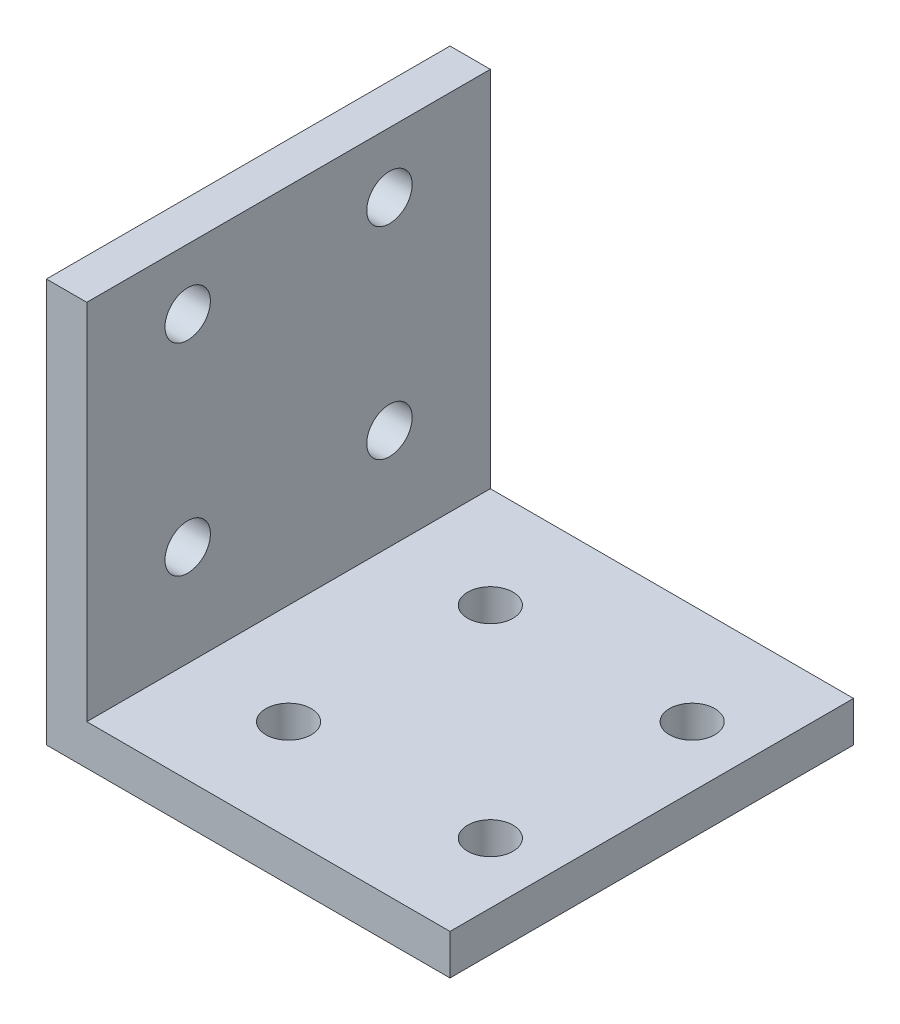
SolidWorks part; units mm, degrees
material "Д16Т ГОСТ 4784-74"
ref_plane "Спереди" through (0, 0, 0) normal (0, 0, 1) x (1, 0, 0)
ref_plane "Сверху" through (0, 0, 0) normal (0, 1, 0) x (1, 0, 0)
ref_plane "Справа" through (0, 0, 0) normal (1, 0, 0) x (0, 0, -1)
sketch "Эскиз1" plane through (0, 0, 0) normal (0, 0, 1) x (1, 0, 0)
  line L0 (0, 0) -> (0, 40)
  line L1 (0, 40) -> (4, 40)
  line L2 (4, 40) -> (4, 4)
  line L3 (4, 4) -> (40, 4)
  line L4 (40, 4) -> (40, 0)
  line L5 (40, 0) -> (0, 0)
  dimension "D1" = 40
  dimension "D2" = 4
extrude "Бобышка-Вытянуть1" add sketch "Эскиз1" along normal blind 40
hole_wizard "Отверстие с зазором M41" positions "Эскиз3" profile "Эскиз4" hole size "M4" standard "DIN"
sketch "Эскиз3" plane through (0, 4, 0) normal (0, 1, 0) x (-1, 0, 0)
  line L0 (-40, 0) -> (-4, 0) construction
  line L1 (-40, 40) -> (-40, 0) construction
  point P0 (-34, 10)
  point P14 (-14, 10)
  point P15 (-34, 30)
  point P16 (-14, 30)
  dimension "D1" = 10
  dimension "D2" = 6
  dimension "D3" = 2
  dimension "D4" = 2
sketch "Эскиз4" plane through (34, 4, 10) normal (1, 0, 0) x (0, 0, 1)
  line L0 (0, 0) -> (0, 6.3519)
  line L1 (0, 6.3519) -> (2.25, 5)
  line L2 (2.25, 5) -> (2.25, 0)
  line L5 (2.25, 0) -> (0, 0)
  line L10 (0, 6.3519) -> (-2.25, 5) construction
  line L11 (0, -6.35) -> (0, 107.95) construction
  dimension "Диаметр отверстия" = 4.5
  dimension "Глубина отверстия" = 5
  dimension "Угол заточки сверла" = 118
hole_wizard "Отверстие с зазором M42" positions "Эскиз6" profile "Эскиз5" hole size "M4" standard "DIN"
sketch "Эскиз6" plane through (4, 0, 0) normal (1, 0, 0) x (0, 0, -1)
  line L0 (-40, 40) -> (0, 40) construction
  line L1 (0, 40) -> (0, 0) construction
  point P0 (-10, 34)
  point P11 (-30, 34)
  point P12 (-10, 14)
  point P13 (-30, 14)
  dimension "D1" = 6
  dimension "D2" = 10
  dimension "D3" = 2
  dimension "D4" = 2
sketch "Эскиз5" plane through (4, 34, 10) normal (0, 1, 0) x (0, 0, -1)
  line L0 (0, 0) -> (0, 6.3519)
  line L1 (0, 6.3519) -> (2.25, 5)
  line L2 (2.25, 5) -> (2.25, 0)
  line L5 (2.25, 0) -> (0, 0)
  line L10 (0, 6.3519) -> (-2.25, 5) construction
  line L11 (0, -6.35) -> (0, 107.95) construction
  dimension "Диаметр отверстия" = 4.5
  dimension "Глубина отверстия" = 5
  dimension "Угол заточки сверла" = 118
